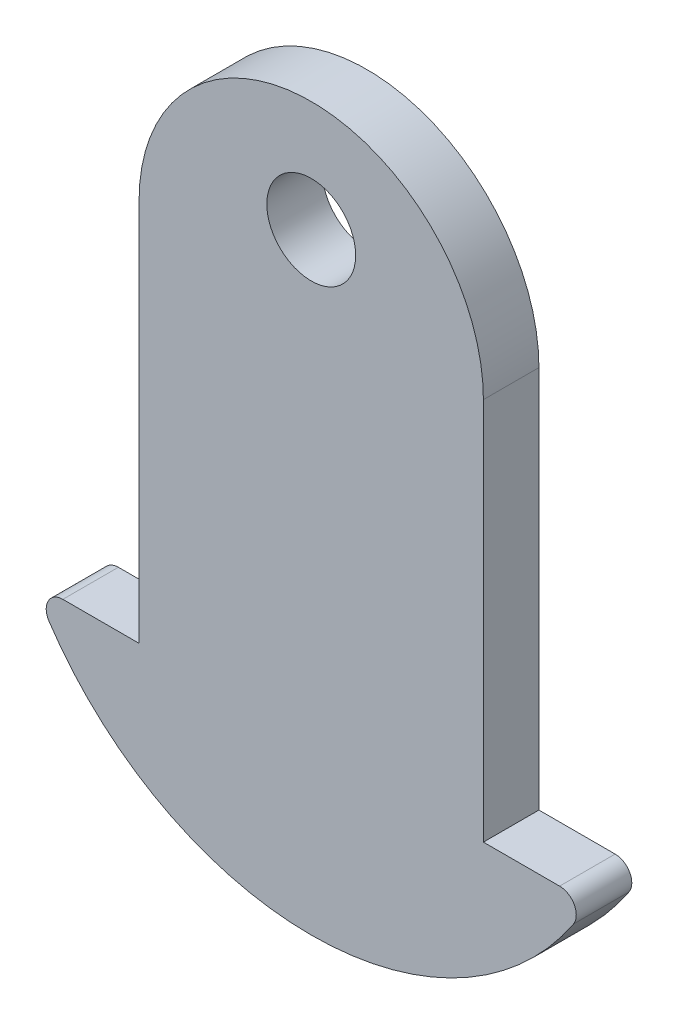
SolidWorks part; units mm, degrees
material "Teak"
ref_plane "Front Plane" through (0, 0, 0) normal (0, 0, 1) x (1, 0, 0)
ref_plane "Top Plane" through (0, 0, 0) normal (0, 1, 0) x (1, 0, 0)
ref_plane "Right Plane" through (0, 0, 0) normal (1, 0, 0) x (0, 0, -1)
sketch "Sketch1" plane through (0, 0, 0) normal (0, 0, 1) x (1, 0, 0)
  line L0 (0, -11.5552) -> (0, 17.25) construction
  line L1 (7.75, 17.25) -> (7.75, 0)
  line L2 (7.75, 0) -> (12.5, 0)
  line L3 (-7.75, 0) -> (-12.5, 0)
  line L4 (-7.75, 17.25) -> (-7.75, 0)
  arc A0 (12.5, 0) -> (-12.5, 0) centre (0, 6.6667) cw
  arc A1 (7.75, 17.25) -> (-7.75, 17.25) centre (0, 17.25) ccw
  circle A4 centre (0, 20) radius 2
  point P9 (0, 25)
  dimension "D1" = 15.5
  dimension "D2" = 25
  dimension "D8" = 4
  dimension "D3" = 7.5
  dimension "D4" = 25
  dimension "D9" = 20
extrude "Boss-Extrude1" add sketch "Sketch1" along normal mid plane 2.5
fillet "Fillet1" radius 0.75 2 edges at (-12.5, 0, 0) (12.5, 0, 0)
fillet "Fillet3" [suppressed] radius 0.5
